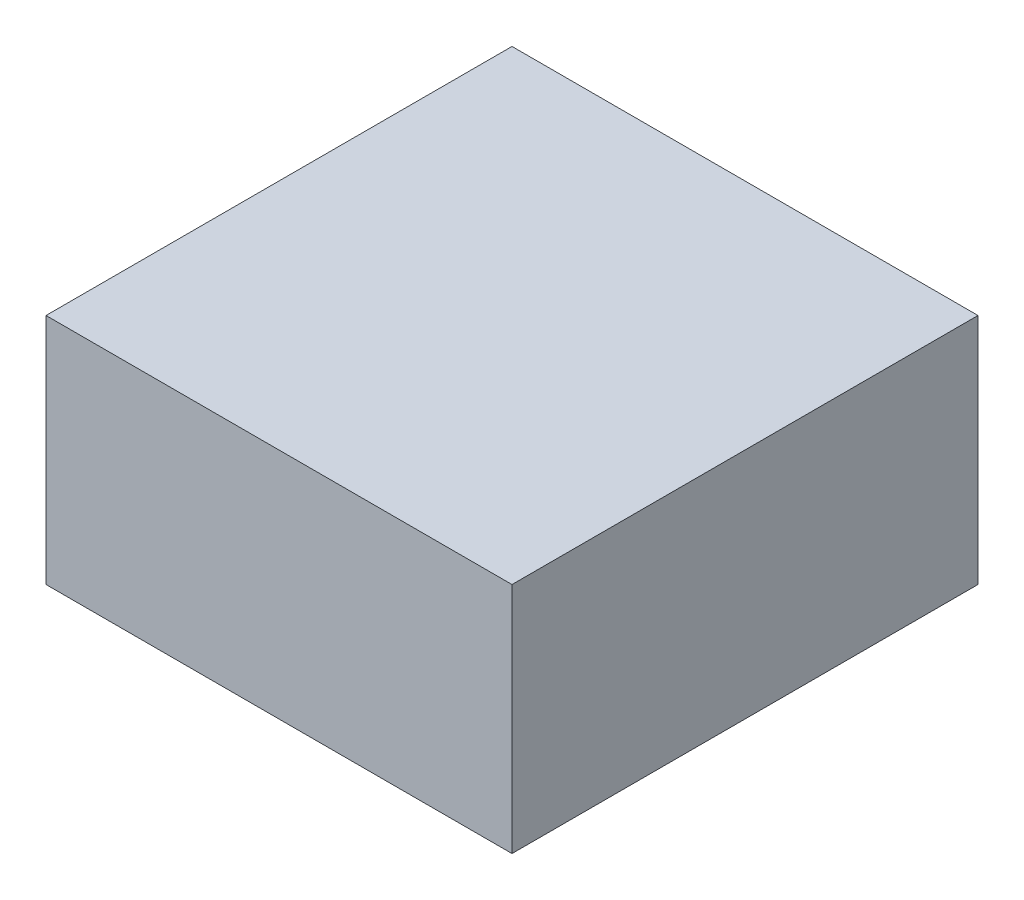
SolidWorks part; units mm, degrees
ref_plane "Front Plane" through (0, 0, 0) normal (0, 0, 1) x (1, 0, 0)
ref_plane "Top Plane" through (0, 0, 0) normal (0, 1, 0) x (1, 0, 0)
ref_plane "Right Plane" through (0, 0, 0) normal (1, 0, 0) x (0, 0, -1)
sketch "Sketch1" plane through (0, 0, 0) normal (1, 0, 0) x (0, 0, -1)
  line L1 (0, 0) -> (10, 0)
  line L2 (0, 0) -> (0, 5)
  line L3 (0, 5) -> (10, 5)
  line L4 (10, 0) -> (10, 5)
  dimension "D1" = 5
  dimension "D2" = 10
extrude "Boss-Extrude1" add sketch "Sketch1" along normal blind 10
